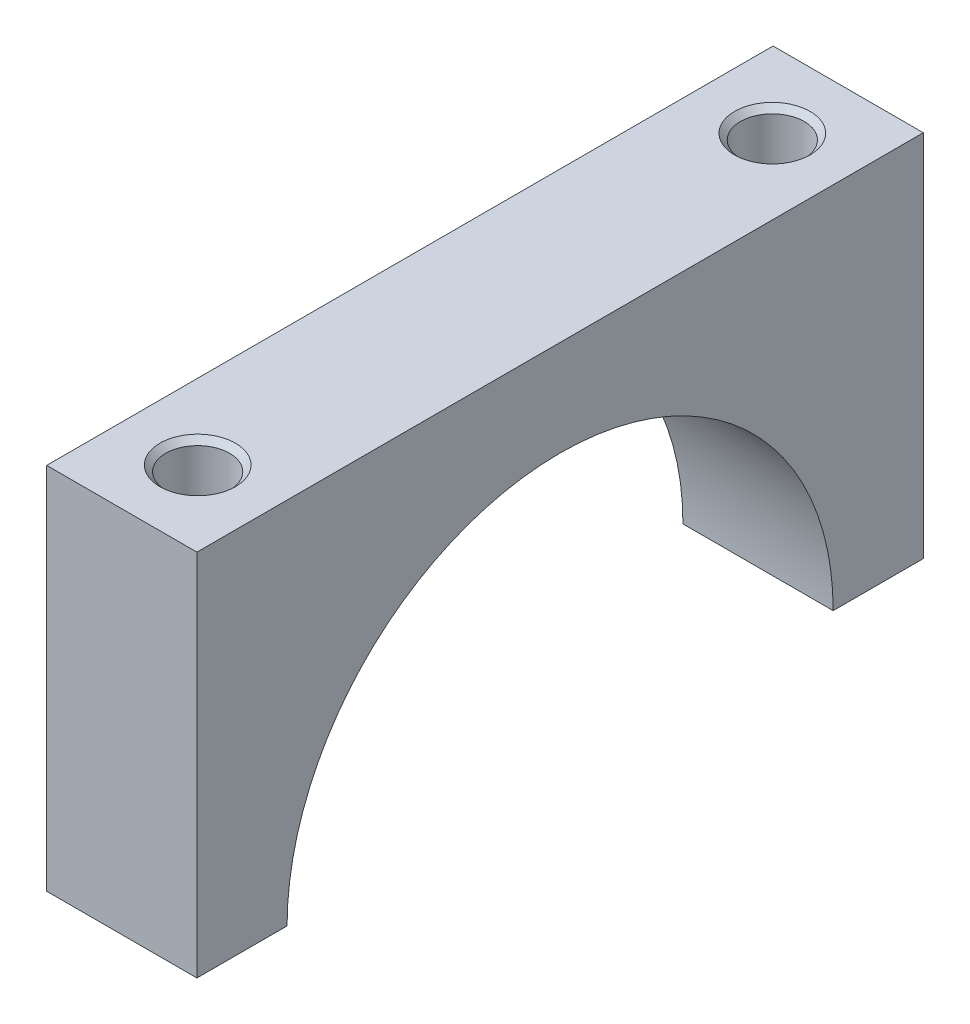
SolidWorks part; units mm, degrees
material "2014 Alloy"
ref_plane "Front Plane" through (0, 0, 0) normal (0, 0, 1) x (1, 0, 0)
ref_plane "Top Plane" through (0, 0, 0) normal (0, 1, 0) x (1, 0, 0)
ref_plane "Right Plane" through (0, 0, 0) normal (1, 0, 0) x (0, 0, -1)
sketch "Sketch1" plane through (0, 0, 0) normal (1, 0, 0) x (0, 0, -1)
  line L0 (-48.35, 0) -> (48.35, 0)
  line L1 (48.35, 0) -> (48.35, -49.098)
  line L2 (48.35, -49.098) -> (36.35, -49.098)
  line L3 (0, 0) -> (0, -49.098) construction
  line L4 (-48.35, -49.098) -> (-36.35, -49.098)
  line L5 (-48.35, 0) -> (-48.35, -49.098)
  arc A0 (36.35, -49.098) -> (-36.35, -49.098) centre (0, -49.098) ccw
  dimension "D1" = 36.35
  dimension "D2" = 12
  dimension "D3" = 49.098
extrude "Boss-Extrude1" add sketch "Sketch1" along normal blind 20
hole_wizard "M8 Tapped Hole1" positions "Sketch3" profile "Sketch2" tap size "M8" standard "ISO"
sketch "Sketch3" plane through (0, -49.098, 0) normal (0, -1, 0) x (-1, 0, 0)
  line L0 (-10, -48.35) -> (-10, -36.35) construction
  line L1 (-20, -48.35) -> (0, -48.35) construction
  line L2 (-20, -36.35) -> (0, -36.35) construction
  line L3 (-10, -36.35) -> (-10, 36.35) construction
  line L4 (-20, 36.35) -> (0, 36.35) construction
  line L5 (-10, 36.35) -> (-10, 48.35) construction
  line L6 (-20, 48.35) -> (0, 48.35) construction
  point P0 (-10, -42.35)
  point P2 (-10, 42.35)
sketch "Sketch2" plane through (10, -49.098, 42.35) normal (1, 0, 0) x (0, 0, -1)
  line L0 (0, 0) -> (0, 32.0429)
  line L1 (0, 32.0429) -> (3.4, 30)
  line L2 (3.4, 30) -> (3.4, 0.625)
  line L3 (3.4, 0.625) -> (4.025, 0)
  line L5 (4.025, 0) -> (0, 0)
  line L6 (-3.4, 0.625) -> (-4.025, 0) construction
  line L10 (0, 32.0429) -> (-3.4, 30) construction
  line L11 (0, -6.35) -> (0, 107.95) construction
  dimension "Tap Drill Dia." = 6.8
  dimension "Tap Drill Depth" = 30
  dimension "Near C'Sink Dia." = 8.05
  dimension "Near C'Sink Angle" = 90
  dimension "Drill Angle" = 118
hole_wizard "M10 Tapped Hole1" positions "Sketch5" profile "Sketch4" tap size "M10" standard "ISO"
sketch "Sketch5" plane through (0, 0, 0) normal (0, 1, 0) x (1, 0, 0)
  line L0 (10, -48.35) -> (10, -38.25) construction
  line L1 (20, -48.35) -> (0, -48.35) construction
  line L2 (10, -38.25) -> (10, 38.25) construction
  line L3 (10, 38.25) -> (10, 48.35) construction
  line L4 (20, 48.35) -> (0, 48.35) construction
  line L5 (10, 48.35) -> (20, 38.25) construction
  line L6 (20, 48.35) -> (20, -48.35) construction
  line L7 (20, 38.25) -> (10, 38.25) construction
  point P0 (10, -38.25)
  point P2 (10, 38.25)
  dimension "D1" = 76.5
sketch "Sketch4" plane through (10, 0, 38.25) normal (1, 0, 0) x (0, 0, 1)
  line L0 (0, 0) -> (0, 30.0537)
  line L1 (0, 30.0537) -> (4.25, 27.5)
  line L2 (4.25, 27.5) -> (4.25, 0.775)
  line L3 (4.25, 0.775) -> (5.025, 0)
  line L5 (5.025, 0) -> (0, 0)
  line L6 (-4.25, 0.775) -> (-5.025, 0) construction
  line L10 (0, 30.0537) -> (-4.25, 27.5) construction
  line L11 (0, -6.35) -> (0, 107.95) construction
  dimension "Tap Drill Dia." = 8.5
  dimension "Tap Drill Depth" = 27.5
  dimension "Near C'Sink Dia." = 10.05
  dimension "Near C'Sink Angle" = 90
  dimension "Drill Angle" = 118
sketch "Sketch6" [suppressed] plane through (0, 0, 0) normal (-1, 0, 0) x (0, 0, 1)
  line L5 (48.25, -49.12) -> (48.25, 0)
  line L6 (48.25, 0) -> (-48.25, 0)
  line L7 (-48.25, 0) -> (-48.25, -49.12)
  line L8 (-48.25, -49.12) -> (-36.25, -49.12)
  line L9 (36.25, -49.12) -> (48.25, -49.12)
  line L10 (48.25, -49.12) -> (48.25, 0)
  line L11 (48.25, 0) -> (-48.25, 0)
  line L12 (-48.25, 0) -> (-48.25, -49.12)
  line L13 (-48.25, -49.12) -> (-36.25, -49.12)
  line L14 (36.25, -49.12) -> (48.25, -49.12)
  arc A1 (36.25, -49.12) -> (-36.25, -49.12) centre (0, -49.12) ccw
  arc A2 (36.25, -49.12) -> (-36.25, -49.12) centre (0, -49.12) ccw
  dimension "D1" = 0
extrude "Boss-Extrude2" [suppressed] add sketch "Sketch6" along normal blind 5
sketch "Sketch7" [suppressed] plane through (-5, 0, 0) normal (-1, 0, 0) x (0, 0, 1)
  line L0 (35.2358, -50.12) -> (49.25, -50.12)
  line L1 (49.25, -50.12) -> (49.25, 1)
  line L2 (49.25, 1) -> (-49.25, 1)
  line L3 (-49.25, 1) -> (-49.25, -50.12)
  line L4 (-49.25, -50.12) -> (-35.2358, -50.12)
  line L5 (36.25, -49.12) -> (48.25, -49.12)
  line L6 (48.25, -49.12) -> (48.25, 0)
  line L7 (48.25, 0) -> (-48.25, 0)
  line L8 (-48.25, 0) -> (-48.25, -49.12)
  line L9 (-48.25, -49.12) -> (-36.25, -49.12)
  line L10 (36.25, -49.12) -> (48.25, -49.12)
  line L11 (48.25, -49.12) -> (48.25, 0)
  line L12 (48.25, 0) -> (-48.25, 0)
  line L13 (-48.25, 0) -> (-48.25, -49.12)
  line L14 (-48.25, -49.12) -> (-36.25, -49.12)
  arc A0 (35.2358, -50.12) -> (-35.2358, -50.12) centre (0, -49.12) ccw
  arc A1 (36.25, -49.12) -> (-36.25, -49.12) centre (0, -49.12) ccw
  arc A2 (36.25, -49.12) -> (-36.25, -49.12) centre (0, -49.12) ccw
  dimension "D1" = 0
  dimension "D2" = 1
extrude "Boss-Extrude3" [suppressed] add sketch "Sketch7" against normal blind 25
